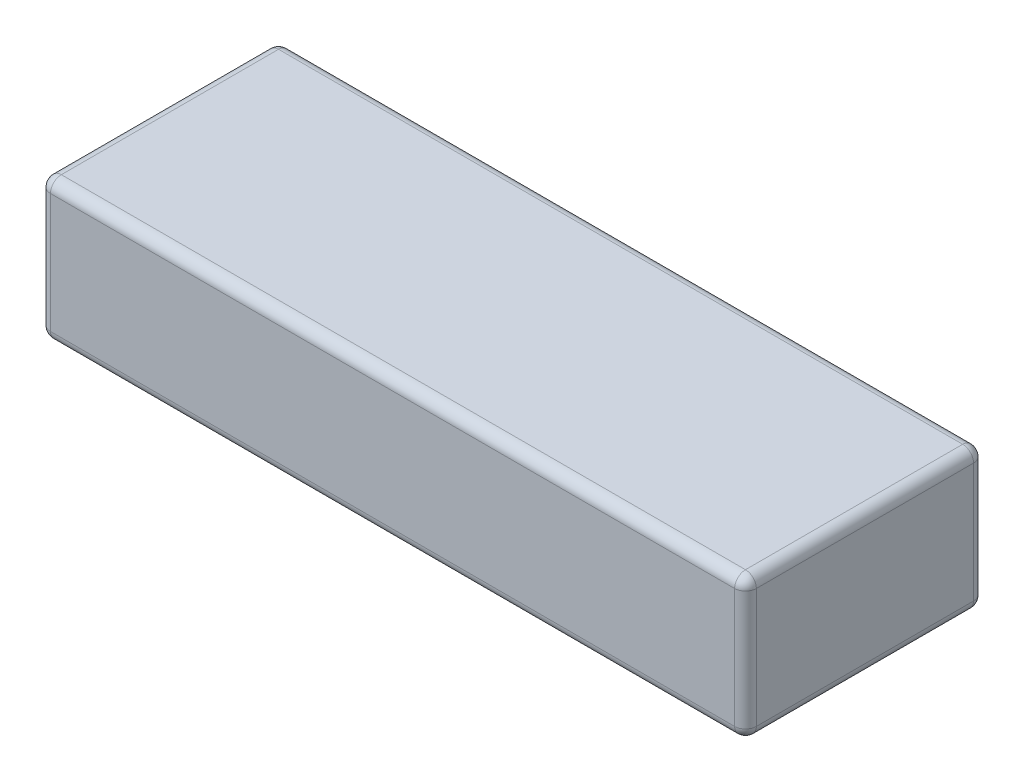
SolidWorks part; units mm, degrees
ref_plane "Front Plane" through (0, 0, 0) normal (0, 0, 1) x (1, 0, 0)
ref_plane "Top Plane" through (0, 0, 0) normal (0, 1, 0) x (1, 0, 0)
ref_plane "Right Plane" through (0, 0, 0) normal (1, 0, 0) x (0, 0, -1)
sketch "Sketch1" plane through (0, 0, 0) normal (0, 1, 0) x (1, 0, 0)
  line L1 (-61.7928, 27.4293) -> (68.2072, 27.4293)
  line L2 (-61.7928, 27.4293) -> (-61.7928, -16.5707)
  line L3 (-61.7928, -16.5707) -> (68.2072, -16.5707)
  line L4 (68.2072, 27.4293) -> (68.2072, -16.5707)
  dimension "D1" = 130
  dimension "D2" = 44
extrude "Boss-Extrude1" add sketch "Sketch1" along normal blind 26
fillet "Fillet1" radius 2 12 edges at (-61.7928, 13, 16.5707) (-61.7928, 0, -5.4293) (3.2072, 26, -27.4293) (-61.7928, 26, -5.4293) (-61.7928, 13, -27.4293) (3.2072, 0, -27.4293) (68.2072, 13, -27.4293) (3.2072, 0, 16.5707) (68.2072, 0, -5.4293) (68.2072, 13, 16.5707) (68.2072, 26, -5.4293) (3.2072, 26, 16.5707)
